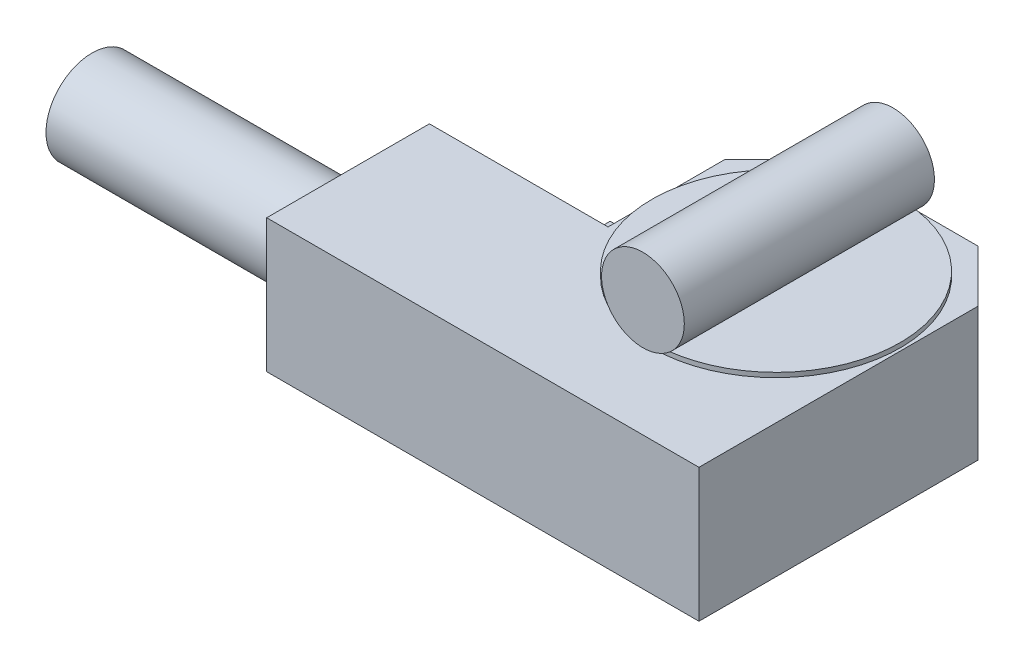
SolidWorks part; units mm, degrees
ref_plane "Front Plane" through (0, 0, 0) normal (0, 0, 1) x (1, 0, 0)
ref_plane "Top Plane" through (0, 0, 0) normal (0, 1, 0) x (1, 0, 0)
ref_plane "Right Plane" through (0, 0, 0) normal (1, 0, 0) x (0, 0, -1)
sketch "Sketch1" plane through (0, 0, 0) normal (0, 1, 0) x (1, 0, 0)
  line L0 (0, 0) -> (47, 0)
  line L1 (47, 0) -> (47, 30.3431)
  line L2 (47, 30.3431) -> (41.3431, 36)
  line L3 (41.3431, 36) -> (25.069, 36)
  line L4 (25.069, 36) -> (19.4121, 30.3431)
  line L5 (19.4121, 30.3431) -> (7, 30.3431)
  line L6 (7, 30.3431) -> (7, 17.6918)
  line L7 (7, 17.6918) -> (0, 17.6918)
  line L8 (0, 17.6918) -> (0, 0)
  dimension "D1" = 47
  dimension "D2" = 36
  dimension "D3" = 135
  dimension "D4" = 8
  dimension "D5" = 8
  dimension "D6" = 135
  dimension "D7" = 40
extrude "Boss-Extrude1" add sketch "Sketch1" along normal blind 14.5
sketch "Sketch2" plane through (0, 14.5, 0) normal (0, 1, 0) x (1, 0, 0)
  line L1 (7, 30.3431) -> (19.4228, 30.3431)
  line L2 (7, 30.3431) -> (7, 17.6918)
  line L3 (7, 17.6918) -> (19.4228, 17.6918)
  line L4 (19.4228, 30.3431) -> (19.4228, 17.6918)
extrude "Cut-Extrude1" cut sketch "Sketch2" against normal blind 12
sketch "Sketch3" plane through (0, 2.5, 0) normal (0, 1, 0) x (1, 0, 0)
  line L0 (7, 30.3431) -> (19.4228, 17.6918) construction
  line L1 (19.4121, 30.3431) -> (7, 17.6918) construction
  circle A0 centre (10.2114, 27.0175) radius 1.1
  circle A1 centre (16.1493, 27.0175) radius 1.1
  circle A2 centre (10.2114, 20.9651) radius 1.1
  circle A3 centre (16.1493, 21.0255) radius 1.1
  point P11 (13.2114, 24.0175)
  dimension "D3" = 2.2
  dimension "D1" = 3
  dimension "D2" = 3
extrude "Cut-Extrude2" cut sketch "Sketch3" against normal through all
sketch "Sketch4" plane through (0, 0, 0) normal (-1, 0, 0) x (0, 0, 1)
  line L0 (0, 14.5) -> (0, 0) construction
  circle A0 centre (-8, 7.515) radius 5
  dimension "D1" = 8
extrude "Boss-Extrude2" add sketch "Sketch4" along normal blind 27
sketch "Sketch5" plane through (0, 14.5, 0) normal (0, 1, 0) x (1, 0, 0)
  circle A0 centre (33.2046, 22.1747) radius 13.5
  dimension "D1" = 27
extrude "Boss-Extrude3" add sketch "Sketch5" along normal blind 0.5
sketch "Sketch6" plane through (0, 15, 0) normal (0, 1, 0) x (1, 0, 0)
  line L1 (28.7046, 34.9026) -> (37.7046, 34.9026)
  line L2 (28.7046, 34.9026) -> (28.7046, 7.7044)
  line L3 (28.7046, 7.7044) -> (37.7046, 7.7044)
  line L4 (37.7046, 34.9026) -> (37.7046, 7.7044)
  circle A0 centre (33.2046, 22.1747) radius 13.5 construction
  circle A1 centre (33.2046, 22.1747) radius 13.5 construction
  point P6 (33.2046, 34.9026)
  dimension "D1" = 9
  dimension "D2" = 0
extrude "Boss-Extrude4" add sketch "Sketch6" along normal blind 9
sketch "Sketch7" plane through (0, 0, -7.7044) normal (0, 0, 1) x (1, 0, 0)
  line L1 (28.7046, 24) -> (37.7046, 24)
  line L2 (28.7046, 24) -> (28.7046, 15)
  line L3 (28.7046, 15) -> (37.7046, 15)
  line L4 (37.7046, 24) -> (37.7046, 15)
  circle A0 centre (33.2046, 19.5) radius 4.5
  line M1 (28.7046, 15) -> (37.7046, 15)
  line M2 (37.7046, 15) -> (37.7046, 24)
  line M3 (37.7046, 24) -> (28.7046, 24)
  line M4 (28.7046, 24) -> (28.7046, 15)
extrude "Cut-Extrude3" cut sketch "Sketch7" against normal through all contours A0 L1 M4 | A0 L4 M3 | A0 L3 M2 | A0 L2 M1
